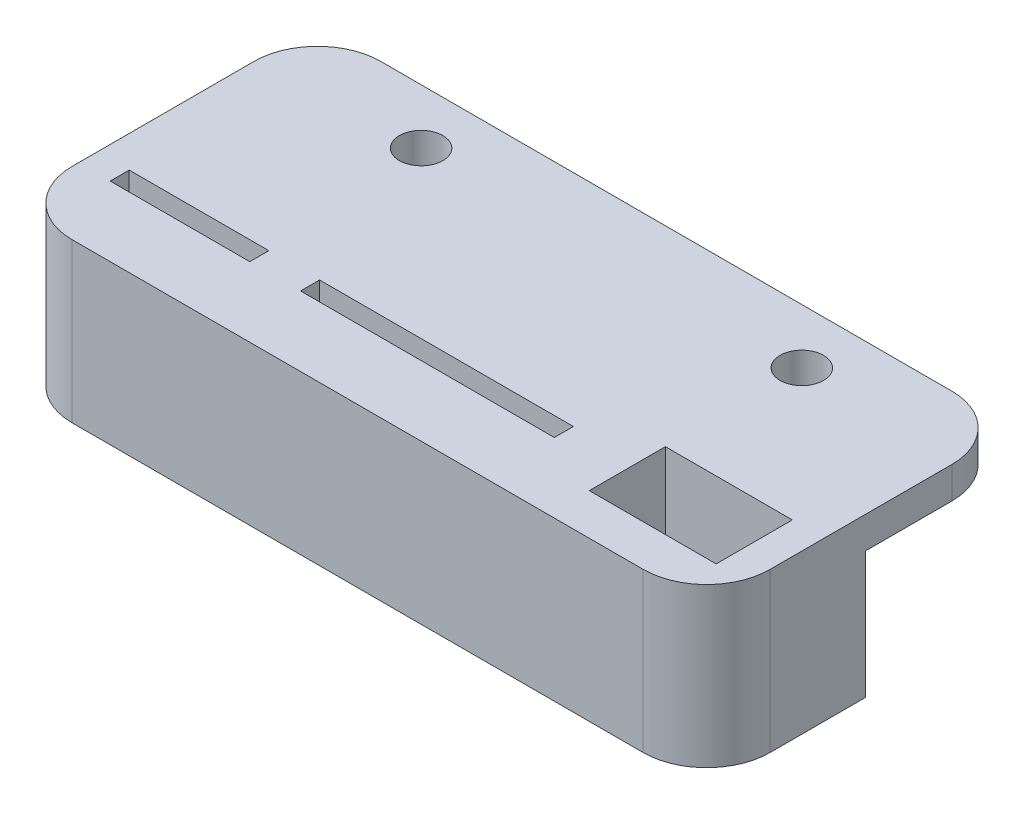
SolidWorks part; units mm, degrees
ref_plane "Front" through (0, 0, 0) normal (0, 0, 1) x (1, 0, 0)
ref_plane "Top" through (0, 0, 0) normal (0, 1, 0) x (1, 0, 0)
ref_plane "Right" through (0, 0, 0) normal (1, 0, 0) x (0, 0, -1)
sketch "Sketch1" plane through (0, 0, 0) normal (0, 1, 0) x (1, 0, 0)
  line L1 (-55, -15) -> (55, -15)
  line L2 (-55, -15) -> (-55, 15)
  line L3 (-55, 15) -> (55, 15)
  line L4 (55, -15) -> (55, 15)
  line L5 (-55, -15) -> (55, 15) construction
  line L6 (-55, 15) -> (55, -15) construction
  point P0 (0, 0)
  dimension "D1" = 30
  dimension "D2" = 110
extrude "Boss-Extrude1" add sketch "Sketch1" along normal blind 5
sketch "Sketch2" plane through (0, 0, 15) normal (0, 0, 1) x (1, 0, 0)
  line L1 (-55, 5) -> (55, 5)
  line L2 (-55, 5) -> (-55, -20)
  line L3 (-55, -20) -> (55, -20)
  line L4 (55, 5) -> (55, -20)
  dimension "D1" = 25
extrude "Boss-Extrude2" add sketch "Sketch2" along normal blind 25
sketch "Sketch6" plane through (0, 5, 0) normal (0, 1, 0) x (1, 0, 0)
  line L0 (30, 0) -> (-30, 0) construction
  circle A0 centre (-30, 0) radius 3.429
  circle A1 centre (30, 0) radius 3.429
  point P4 (0, 0)
  dimension "D1" = 6.858
  dimension "D2" = 60
extrude "Cut-Extrude4" cut sketch "Sketch6" against normal through all
sketch "Sketch7" plane through (0, 5, 0) normal (0, 1, 0) x (1, 0, 0)
  line L0 (55, -40) -> (55, -15) construction
  line L1 (55, -40) -> (55, -15) construction
  line L2 (50, -27.5) -> (-49950, -27.5) construction
  line L3 (-55, 15) -> (-55, -40) construction
  line L4 (20, -29) -> (-20, -29)
  line L5 (20, -29) -> (20, -26)
  line L6 (20, -26) -> (-20, -26)
  line L7 (-20, -29) -> (-20, -26)
  line L8 (20, -29) -> (-20, -26) construction
  line L9 (20, -26) -> (-20, -29) construction
  line L10 (50, -33.5) -> (30, -33.5)
  line L11 (50, -33.5) -> (50, -21.5)
  line L12 (50, -21.5) -> (30, -21.5)
  line L13 (30, -33.5) -> (30, -21.5)
  line L14 (50, -33.5) -> (30, -21.5) construction
  line L15 (50, -21.5) -> (30, -33.5) construction
  line L16 (-28, -29) -> (-50, -29)
  line L17 (-28, -29) -> (-28, -26)
  line L18 (-28, -26) -> (-50, -26)
  line L19 (-50, -29) -> (-50, -26)
  line L20 (-28, -29) -> (-50, -26) construction
  line L21 (-28, -26) -> (-50, -29) construction
  point P4 (55, -27.5)
  point P5 (0, -27.5)
  point P10 (40, -27.5)
  point P15 (-39, -27.5)
  dimension "D1" = 20
  dimension "D2" = 12
  dimension "D3" = 5
  dimension "D4" = 10
  dimension "D5" = 40
  dimension "D6" = 5
  dimension "D7" = 22
  dimension "D8" = 3
  dimension "D9" = 3
extrude "Cut-Extrude5" cut sketch "Sketch7" against normal through all
sketch "Sketch8" plane through (0, 5, 0) normal (0, 1, 0) x (1, 0, 0)
  line L0 (55, -40) -> (55, 15) construction
  line L1 (-55, 15) -> (55, 15)
  line L2 (-55, 15) -> (-55, 8.65)
  line L3 (-55, 8.65) -> (55, 8.65)
  line L4 (55, 15) -> (55, 8.65)
  dimension "D1" = 6.35
extrude "Cut-Extrude6" cut sketch "Sketch8" against normal through all
fillet "Fillet1" radius 10 4 edges at (-55, -7.5, 40) (-55, 2.5, -8.65) (55, 2.5, -8.65) (55, -7.5, 40)
